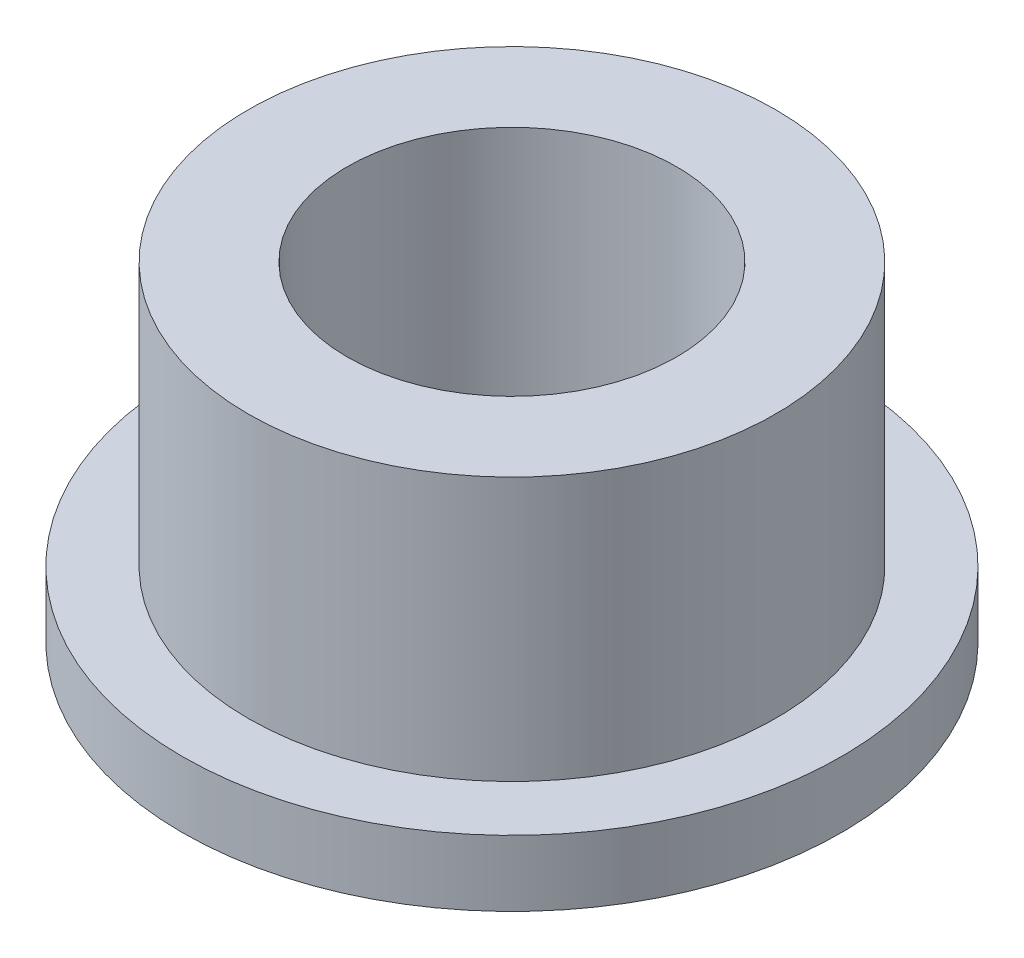
SolidWorks part; units mm, degrees
material "Cast Alloy Steel"
ref_plane "Front Plane" through (0, 0, 0) normal (0, 0, 1) x (1, 0, 0)
ref_plane "Top Plane" through (0, 0, 0) normal (0, 1, 0) x (1, 0, 0)
ref_plane "Right Plane" through (0, 0, 0) normal (1, 0, 0) x (0, 0, -1)
sketch "Sketch1" plane through (0, 0, 0) normal (0, 1, 0) x (1, 0, 0)
  circle A0 centre (0, 0) radius 5
  dimension "D1" = 10
extrude "Boss-Extrude1" add sketch "Sketch1" along normal blind 1
sketch "Sketch2" plane through (0, 1, 0) normal (0, 1, 0) x (1, 0, 0)
  circle A0 centre (0, 0) radius 4
  dimension "D1" = 8
extrude "Boss-Extrude4" add sketch "Sketch2" along normal blind 4
cosmetic thread "Cosmetic Thread2" parameters "D1"=4, "D2"=6.619
sketch "Sketch5" plane through (0, 5, 0) normal (0, 1, 0) x (1, 0, 0)
  circle A0 centre (0, 0) radius 2.5
  dimension "D1" = 5
extrude "Cut-Extrude4" cut sketch "Sketch5" against normal blind 4
sketch "Sketch6" plane through (0, 1, 0) normal (0, 1, 0) x (1, 0, 0)
  circle A0 centre (0, 0) radius 1.25
  dimension "D1" = 2.5
extrude "Cut-Extrude5" cut sketch "Sketch6" against normal blind 4
sketch "Sketch7" plane through (0, 0, 0) normal (0, -1, 0) x (1, 0, 0)
  circle A0 centre (0, 0) radius 1.5
  dimension "D1" = 3
extrude "Cut-Extrude6" cut sketch "Sketch7" against normal blind 10
